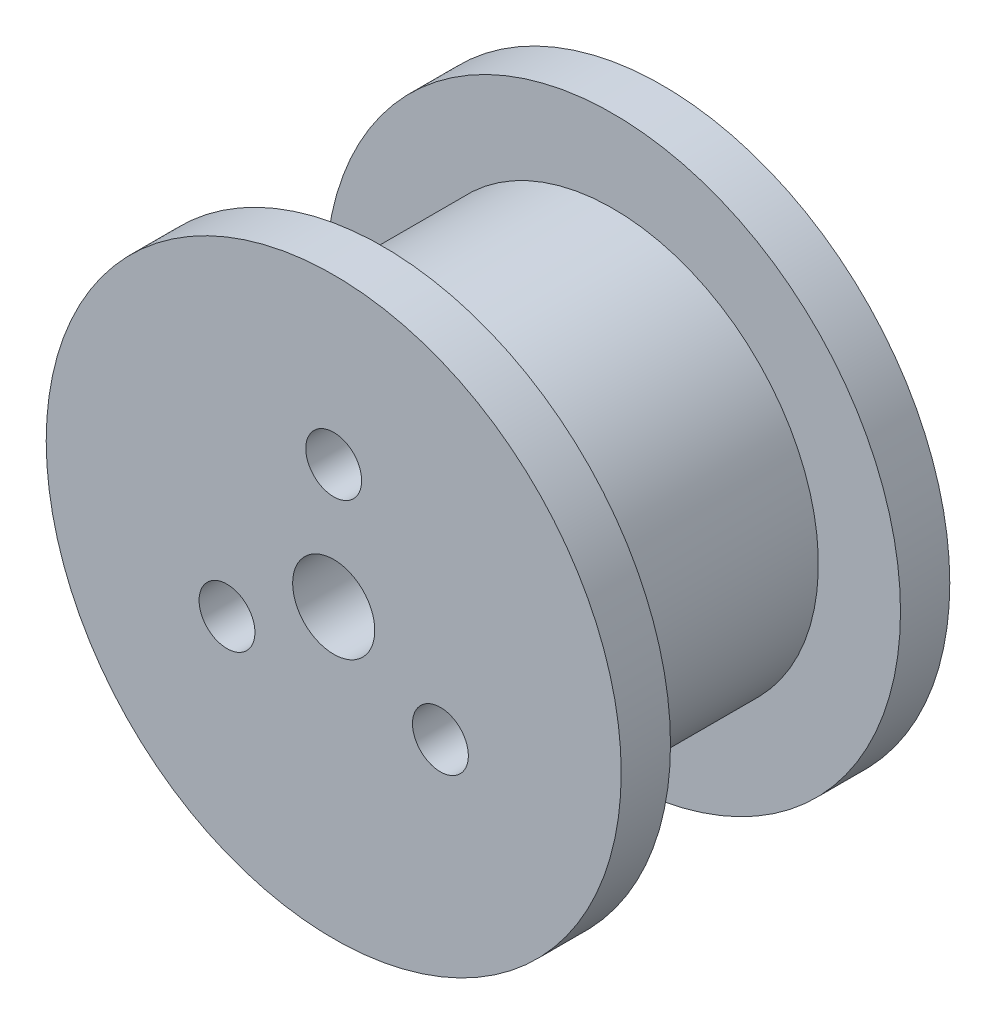
SolidWorks part; units mm, degrees
ref_plane "Plan de face" through (0, 0, 0) normal (0, 0, 1) x (1, 0, 0)
ref_plane "Plan de dessus" through (0, 0, 0) normal (0, 1, 0) x (1, 0, 0)
ref_plane "Plan de droite" through (0, 0, 0) normal (1, 0, 0) x (0, 0, -1)
sketch "Esquisse1" plane through (0, 0, 0) normal (0, 0, 1) x (1, 0, 0)
  circle A0 centre (0, 0) radius 17.5
  dimension "D1" = 35
extrude "Boss.-Extru.1" add sketch "Esquisse1" along normal blind 20
sketch "Esquisse3" plane through (0, 0, 0) normal (1, 0, 0) x (0, 0, -1)
  line L11 (-3, 17.5) -> (-3, 12.5)
  line L12 (0, 17.5) -> (-20, 17.5) construction
  line L13 (-3, 12.5) -> (-17, 12.5)
  line L14 (-17, 12.5) -> (-17, 17.5)
  line L15 (-17, 17.5) -> (-3, 17.5)
  line L16 (-20, 17.5) -> (-20, -17.5) construction
  line L17 (0, -17.5) -> (0, 17.5) construction
  line L18 (0, 0) -> (-20, 0) construction
  dimension "D1" = 3
  dimension "D2" = 3
  dimension "D3" = 5
revolve "Enlèvement de matière-Révolution2" cut sketch "Esquisse3" angle 360 about L18
sketch "Esquisse4" plane through (0, 0, 0) normal (0, 0, -1) x (-1, 0, 0)
  circle A0 centre (0, 0) radius 2.5
  dimension "D1" = 5
extrude "Enlèv. mat.-Extru.1" cut sketch "Esquisse4" against normal blind 20
hole_wizard "Dégagement M31" positions "Esquisse6" profile "Esquisse7" hole size "M3" standard "ISO" end condition through all
sketch "Esquisse6" plane through (0, 0, 0) normal (0, 0, -1) x (-1, 0, 0)
  line L0 (0, 0) -> (0, 12.4144) construction
  point P0 (0, 7.5)
  point P12 (6.4952, -3.75)
  point P13 (-6.4952, -3.75)
  point P14 (0, 0)
  dimension "D1" = 7.5
  dimension "D2" = 3
sketch "Esquisse7" plane through (0, 7.5, 0) normal (1, 0, 0) x (0, 1, 0)
  line L0 (0, 0) -> (0, 20)
  line L1 (0, 20) -> (1.7, 20)
  line L2 (1.7, 20) -> (1.7, 0)
  line L5 (1.7, 0) -> (0, 0)
  line L11 (0, -6.35) -> (0, 107.95) construction
  dimension "Diamètre du perçage jusqu'au prochain" = 3.4
  dimension "Profondeur du perçage jusqu'au prochain" = 20
